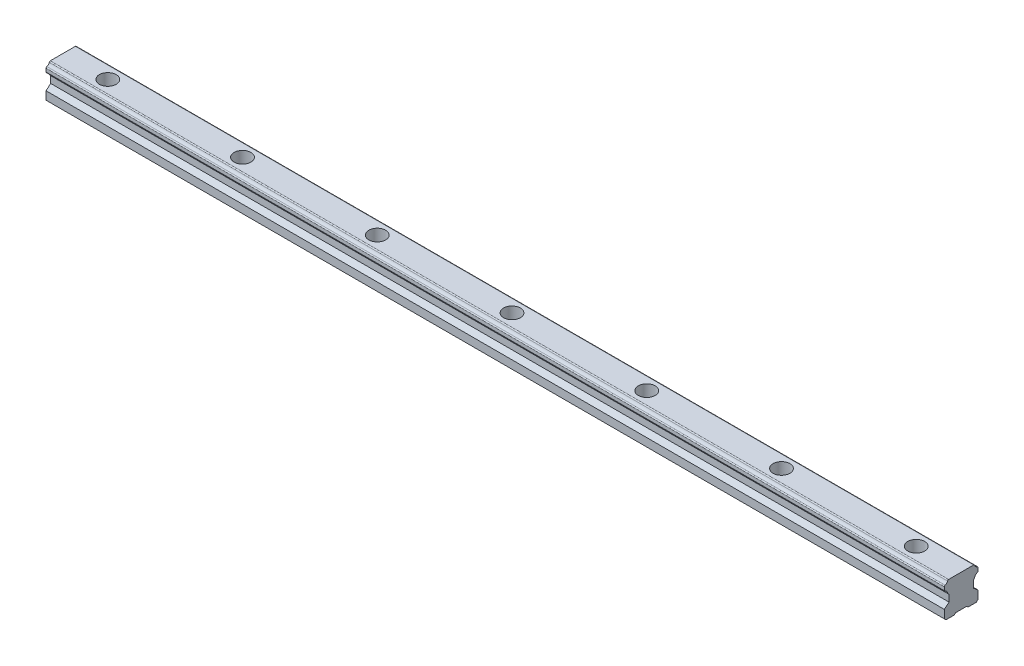
SolidWorks part; units mm, degrees
ref_plane "前视基准面" through (0, 0, 0) normal (0, 0, 1) x (1, 0, 0)
ref_plane "上视基准面" through (0, 0, 0) normal (0, 1, 0) x (1, 0, 0)
ref_plane "右视基准面" through (0, 0, 0) normal (1, 0, 0) x (0, 0, -1)
sketch "草图1" plane through (0, 0, 0) normal (1, 0, 0) x (0, 0, -1)
  line L1 (7.5, -7.5) -> (-7.5, -7.5)
  line L2 (7.5, -7.5) -> (7.5, 7.5)
  line L3 (7.5, 7.5) -> (-7.5, 7.5)
  line L4 (-7.5, -7.5) -> (-7.5, 7.5)
  line L5 (7.5, -7.5) -> (-7.5, 7.5) construction
  line L6 (7.5, 7.5) -> (-7.5, -7.5) construction
  point P0 (0, 0)
  dimension "D1" = 15
  dimension "D2" = 15
extrude "凸台-拉伸1" add sketch "草图1" along normal mid plane 400
chamfer "倒角1" distance 0.75 angle 45 2 edges at (0, -7.5, 7.5) (0, -7.5, -7.5)
sketch "草图2" plane through (200, 0, 0) normal (1, 0, 0) x (0, 0, -1)
  line L0 (0, 0) -> (0, 2.891) construction
  line L2 (-7.5, 7.5) -> (-6, 7.5)
  line L3 (-7.5, 7.5) -> (-7.5, 6)
  line L4 (7.5, 7.5) -> (7.5, 6)
  line L5 (7.5, 7.5) -> (6, 7.5)
  arc A0 (-7.5, 6) -> (-6, 7.5) centre (-7.5, 7.5) ccw
  arc A1 (7.5, 6) -> (6, 7.5) centre (7.5, 7.5) cw
  dimension "D1" = 3
sketch "草图3" plane through (0, 7.5, 0) normal (0, 1, 0) x (1, 0, 0)
  line L0 (-200, 7.5) -> (-200, -7.5) construction
  line L1 (0, 0) -> (-200, 0) construction
  circle A0 centre (-180, 0) radius 3.75
  dimension "D2" = 7.4999
  dimension "D1" = 20
extrude "切除-拉伸2" cut sketch "草图3" against normal blind 5.3
sketch "草图4" plane through (0, 2.2, 0) normal (0, 1, 0) x (1, 0, 0)
  circle A0 centre (-180, 0) radius 2.25
  dimension "D1" = 4.5
extrude "切除-拉伸3" cut sketch "草图4" against normal through all
pattern_linear "阵列(线性)1" count 7 spacing 60 along (1, 0, 0) of "切除-拉伸2", "切除-拉伸3"
extrude "切除-拉伸4" cut sketch "草图2" against normal through all
sketch "草图5" plane through (200, 0, 0) normal (1, 0, 0) x (0, 0, -1)
  line L0 (-6.75, -7.5) -> (6.75, -7.5) construction
  line L1 (-7.5, 6) -> (-6.185, 6) construction
  line L2 (-7.5, 3.75) -> (-6.185, 3.75) construction
  line L3 (-7.5, 6) -> (-7.5, -6.75) construction
  line L4 (-6, 2.25) -> (-5.4, 1.65)
  line L5 (-5.4, 1.65) -> (-5.4, -1.35)
  line L6 (-5.4, -1.35) -> (-7.5, -3.1)
  line L7 (-7.5, 3.75) -> (-7.5, -3.1)
  line L8 (0, 0) -> (0, 2.35) construction
  line L9 (7.5, 3.75) -> (6.185, 3.75) construction
  line L10 (7.5, 6) -> (6.185, 6) construction
  line L11 (7.5, 3.75) -> (7.5, -3.1)
  line L12 (5.4, -1.35) -> (7.5, -3.1)
  line L13 (5.4, 1.65) -> (5.4, -1.35)
  line L14 (6, 2.25) -> (5.4, 1.65)
  arc A0 (-6, 2.25) -> (-7.5, 3.75) centre (-7.5, 2.25) ccw
  arc A3 (-7.5, 6) -> (-6, 7.5) centre (-7.5, 7.5) ccw construction
  arc A4 (6, 2.25) -> (7.5, 3.75) centre (7.5, 2.25) cw
  dimension "D1" = 2.25
  dimension "D2" = 4.4
  dimension "D3" = 135
  dimension "D4" = 10.8
  dimension "D5" = 3
extrude "切除-拉伸5" cut sketch "草图5" against normal through all
fillet "圆角1" radius 0.5 6 edges at (0, 3.75, -7.5) (0, 6, -7.5) (0, 7.5, -6) (0, 7.5, 6) (0, 3.75, 7.5) (0, 6, 7.5)
sketch "草图6" plane through (-200, 0, 0) normal (-1, 0, 0) x (0, 0, 1)
  line L0 (-3.1, -7.5) -> (-2.5, -6.9)
  line L1 (6.75, -7.5) -> (-6.75, -7.5) construction
  line L2 (-2.5, -6.9) -> (2.5, -6.9)
  line L3 (2.5, -6.9) -> (3.1, -7.5)
  line L4 (0, 0) -> (0, -5.803) construction
  line L5 (-3.1, -7.5) -> (3.1, -7.5)
  dimension "D1" = 0.6
  dimension "D2" = 45
  dimension "D3" = 6.2
extrude "切除-拉伸6" cut sketch "草图6" against normal through all
sketch "草图8" plane through (-200, 0, 0) normal (-1, 0, 0) x (0, 0, 1)
  line L0 (-9.2, -7.5) -> (-8.6, -6.9)
  line L1 (6.75, -7.5) -> (3.1, -7.5) construction
  line L2 (-8.6, -6.9) -> (-3.6, -6.9)
  line L3 (-3.6, -6.9) -> (-3, -7.5)
  line L4 (0, 0) -> (0, -2.1868) construction
  line L5 (3.6, -6.9) -> (3, -7.5)
  line L6 (8.6, -6.9) -> (3.6, -6.9)
  line L7 (9.2, -7.5) -> (8.6, -6.9)
  line L8 (-6.1, -6.9) -> (-6.1, -11.8401) construction
  line L9 (-9.2, -7.5) -> (-3, -7.5)
  line L10 (3, -7.5) -> (9.2, -7.5)
  dimension "D1" = 6.2
  dimension "D2" = 0.6
  dimension "D3" = 6
  dimension "D4" = 45
extrude "切除-拉伸7" [suppressed] cut sketch "草图8" against normal through all
